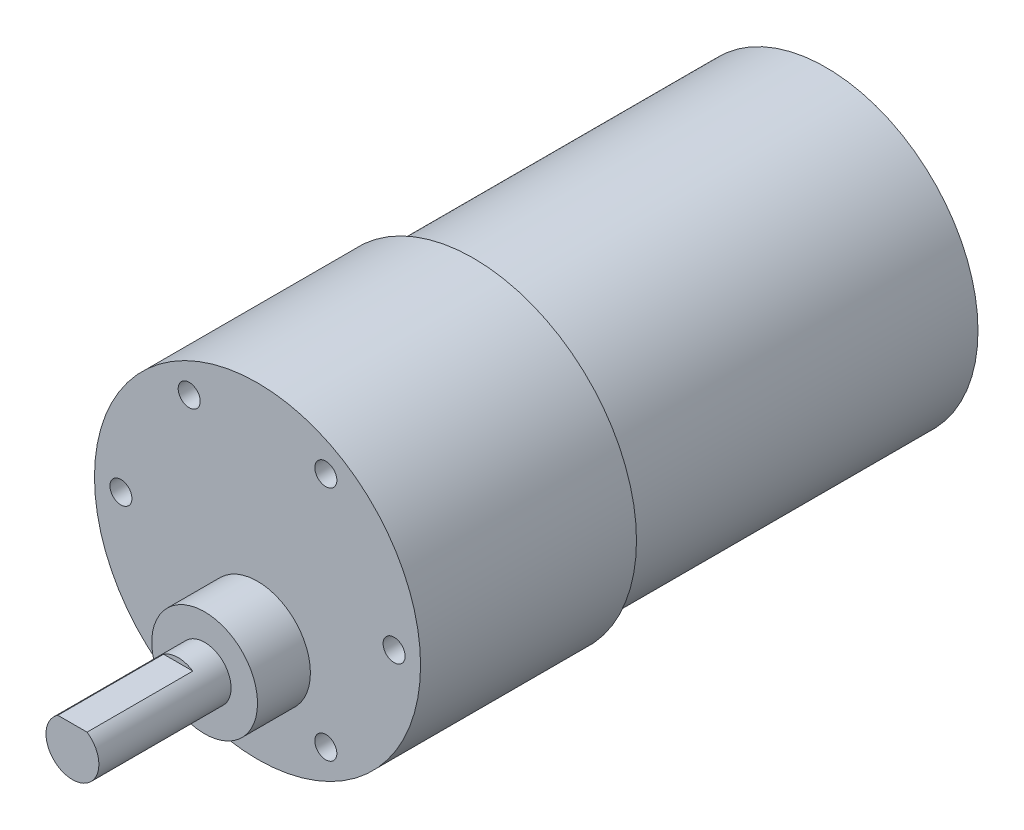
SolidWorks part; units mm, degrees
ref_plane "Front Plane" through (0, 0, 0) normal (0, 0, 1) x (1, 0, 0)
ref_plane "Top Plane" through (0, 0, 0) normal (0, 1, 0) x (1, 0, 0)
ref_plane "Right Plane" through (0, 0, 0) normal (1, 0, 0) x (0, 0, -1)
sketch "Sketch1" plane through (0, 0, 0) normal (0, 0, 1) x (1, 0, 0)
  circle A0 centre (0, 0) radius 17.25
extrude "Boss-Extrude1" add sketch "Sketch1" along normal blind 40
sketch "Sketch2" plane through (0, 0, 40) normal (0, 0, 1) x (1, 0, 0)
  circle A0 centre (0, 0) radius 18.5
extrude "Boss-Extrude2" add sketch "Sketch2" along normal blind 24.5
sketch "Sketch3" plane through (0, 0, 64.5) normal (0, 0, 1) x (1, 0, 0)
  circle A0 centre (0, -7) radius 6
extrude "Boss-Extrude3" add sketch "Sketch3" along normal blind 6
sketch "Sketch4" plane through (0, 0, 70.5) normal (0, 0, 1) x (1, 0, 0)
  circle A0 centre (0, -7) radius 3
extrude "Boss-Extrude4" add sketch "Sketch4" along normal blind 15
sketch "Sketch5" plane through (0, 0, 85.5) normal (0, 0, 1) x (1, 0, 0)
  line L1 (0, -4.5) -> (1.6583, -4.5)
  line L3 (0, -4.5) -> (-1.6583, -4.5)
  circle A0 centre (0, -7) radius 3 construction
  arc A2 (1.6583, -4.5) -> (-1.6583, -4.5) centre (0, -7) ccw
extrude "Cut-Extrude1" cut sketch "Sketch5" against normal blind 12
sketch "Sketch7" plane through (0, 0, 64.5) normal (0, 0, 1) x (1, 0, 0)
  circle A1 centre (-15.5, 0) radius 1.25
  circle A2 centre (-7.75, 13.4234) radius 1.25
  circle A3 centre (7.75, 13.4234) radius 1.25
  circle A4 centre (15.5, 0) radius 1.25
  circle A5 centre (7.75, -13.4234) radius 1.25
  circle A6 centre (-7.75, -13.4234) radius 1.25
  point P16 (0, 0)
  dimension "D1" = 6
  dimension "D2" = 15.5
extrude "Cut-Extrude2" cut sketch "Sketch7" against normal blind 5
